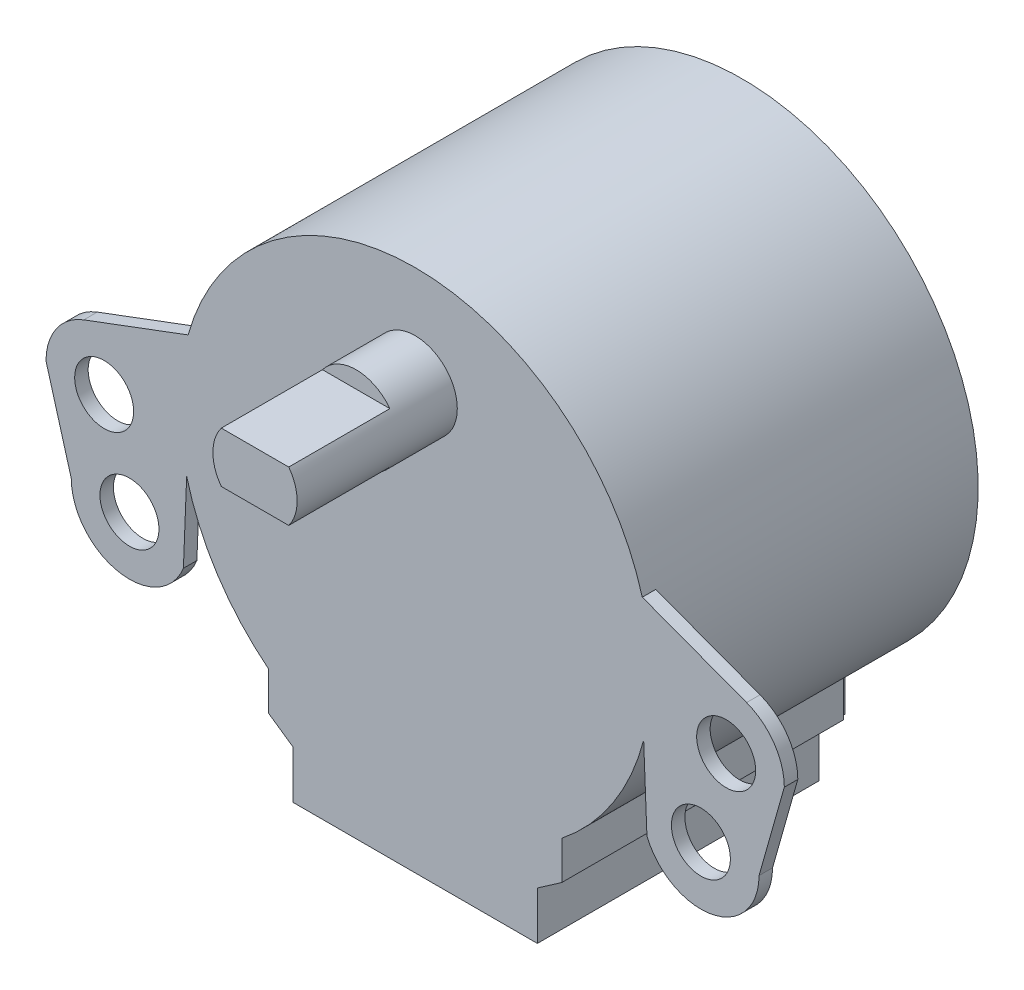
SolidWorks part; units mm, degrees
material "1060 Alloy"
ref_plane "Front Plane" through (0, 0, 0) normal (0, 0, 1) x (1, 0, 0)
ref_plane "Top Plane" through (0, 0, 0) normal (0, 1, 0) x (1, 0, 0)
ref_plane "Right Plane" through (0, 0, 0) normal (1, 0, 0) x (0, 0, -1)
sketch "Sketch2" plane through (0, 0, 0) normal (0, 0, 1) x (1, 0, 0)
  line L1 (-6.1, -15.6012) -> (0, -15.6012)
  line L2 (-6.1, -15.6012) -> (-6.1, -12.6012)
  line L5 (6.1, -15.6012) -> (0, -15.6012)
  line L6 (6.1, -15.6012) -> (6.1, -12.6012)
  arc A0 (6.1, -12.6012) -> (-6.1, -12.6012) centre (0, 0) ccw
  dimension "D2" = 28
  dimension "D1" = 12.2
  dimension "D3" = 3
extrude "Housing Boss-Extrude1" add sketch "Sketch2" against normal blind 19.4
sketch "Sketch4" plane through (0, 0, 0) normal (0, 0, 1) x (1, 0, 0)
  line L0 (0, -17.1012) -> (-7.25, -17.1012)
  line L1 (0, -17.1012) -> (7.25, -17.1012)
  line L2 (7.25, -17.1012) -> (7.25, -14.2532)
  line L3 (-7.25, -17.1012) -> (-7.25, -14.2532)
  line L4 (7.25, -14.2532) -> (8.7, -13.2452)
  line L5 (8.7, -13.2452) -> (8.7, -10.9686)
  line L6 (-7.25, -14.2532) -> (-8.7, -13.2452)
  line L7 (-8.7, -13.2452) -> (-8.7, -10.9686)
  line L8 (-6.1, -12.6012) -> (-6.1, -15.6012)
  line L9 (-6.1, -15.6012) -> (6.1, -15.6012)
  line L10 (6.1, -15.6012) -> (6.1, -12.6012)
  line L11 (0, -17.1012) -> (0, -17.7891) construction
  line L12 (0, -17.7891) -> (-8.7, -17.7891) construction
  line L13 (-8.7, -13.2452) -> (-8.7, -17.7891) construction
  line L14 (8.7, -13.2452) -> (8.7, -17.7891) construction
  line L15 (8.7, -17.7891) -> (0, -17.7891) construction
  line L16 (7.25, -14.2532) -> (7.25, -11.9765) construction
  arc A0 (6.1, -12.6012) -> (8.7, -10.9686) centre (0, 0) ccw
  arc A1 (-8.7, -10.9686) -> (-6.1, -12.6012) centre (0, 0) ccw
  arc A2 (6.1, -12.6012) -> (-6.1, -12.6012) centre (0, 0) ccw construction
  dimension "D1" = 14.5
  dimension "D2" = 1.5
  dimension "D3" = 17.4
  dimension "D4" = 8.7
extrude "Plastic Sheilding Boss-Extrude2" add sketch "Sketch4" against normal blind 16.7
sketch "Sketch5" plane through (0, 0, 0) normal (0, 0, 1) x (1, 0, 0)
  line L0 (13.4744, 3.8) -> (19.6612, 1.4804)
  line L1 (21.9, -1.75) -> (20.4, -7.0415)
  line L2 (0, 29.8443) -> (0, -26.0857) construction
  line L3 (13.749, -8.3283) -> (13.5554, -3.5)
  line L4 (0, 0) -> (38.8665, 0) construction
  line L5 (-13.749, -8.3283) -> (-13.5554, -3.5)
  line L6 (-21.9, -1.75) -> (-20.4, -7.0415)
  line L7 (-13.4744, 3.8) -> (-19.6612, 1.4804)
  line L8 (13.5554, -3.5) -> (24.2178, -3.5) construction
  arc A0 (13.5554, -3.5) -> (13.4744, 3.8) centre (0, 0) ccw
  arc A1 (8.7, -10.9686) -> (-8.7, -10.9686) centre (0, 0) ccw construction
  arc A2 (19.6612, 1.4804) -> (21.9, -1.75) centre (18.45, -1.75) cw
  circle A3 centre (-16.95, -7.0415) radius 1.75
  arc A4 (20.4, -7.0415) -> (13.749, -8.3283) centre (16.95, -7.0415) cw
  circle A5 centre (-18.45, -1.75) radius 1.75
  arc A6 (-20.4, -7.0415) -> (-13.749, -8.3283) centre (-16.95, -7.0415) ccw
  circle A7 centre (18.45, -1.75) radius 1.75
  circle A8 centre (16.95, -7.0415) radius 1.75
  arc A9 (-19.6612, 1.4804) -> (-21.9, -1.75) centre (-18.45, -1.75) ccw
  arc A10 (-13.5554, -3.5) -> (-13.4744, 3.8) centre (0, 0) cw
  dimension "D2" = 3.5
  dimension "D3" = 40.4
  dimension "D1" = 1.7
  dimension "D4" = 1.7
  dimension "D5" = 2
  dimension "D9" = 1.5
  dimension "D6" = 5.5
  dimension "D7" = 7.3
  dimension "D8" = 1.5
  dimension "D10" = 36.9
extrude "Mounting Brackets Boss-Extrude3" add sketch "Sketch5" against normal blind 0.8
sketch "Sketch6" plane through (0, 0, 0) normal (0, 0, 1) x (1, 0, 0)
  circle A0 centre (0, 8) radius 2.5
  dimension "D1" = 5
  dimension "D2" = 8
extrude "Shaft Boss-Extrude4" add sketch "Sketch6" along normal blind 9.5
sketch "Sketch7" plane through (0, 0, 9.5) normal (0, 0, 1) x (1, 0, 0)
  line L0 (-2, 9.5) -> (2, 9.5)
  line L1 (-2, 6.5) -> (2, 6.5)
  arc A0 (2, 9.5) -> (-2, 9.5) centre (0, 8) ccw
  circle A1 centre (0, 8) radius 2.5 construction
  arc A2 (-2, 6.5) -> (2, 6.5) centre (0, 8) ccw
  dimension "D1" = 3
extrude "Shaft EdgeCut-Extrude1" cut sketch "Sketch7" against normal blind 6
sketch "Sketch8" plane through (0, -17.1012, 0) normal (0, -1, 0) x (1, 0, 0)
  line L0 (-7.25, 0) -> (7.25, 0) construction
  line L1 (0, -2) -> (3.25, -2)
  line L3 (0, -3.2) -> (3.25, -3.2)
  line L4 (3.25, -2) -> (3.25, -3.2)
  line L5 (0, -2) -> (-3.25, -2)
  line L7 (0, -3.2) -> (-3.25, -3.2)
  line L8 (-3.25, -2) -> (-3.25, -3.2)
  dimension "D1" = 6.5
  dimension "D2" = 2
  dimension "D3" = 1.2
extrude "Cable Hole Cut-Extrude2" cut sketch "Sketch8" against normal blind 5
